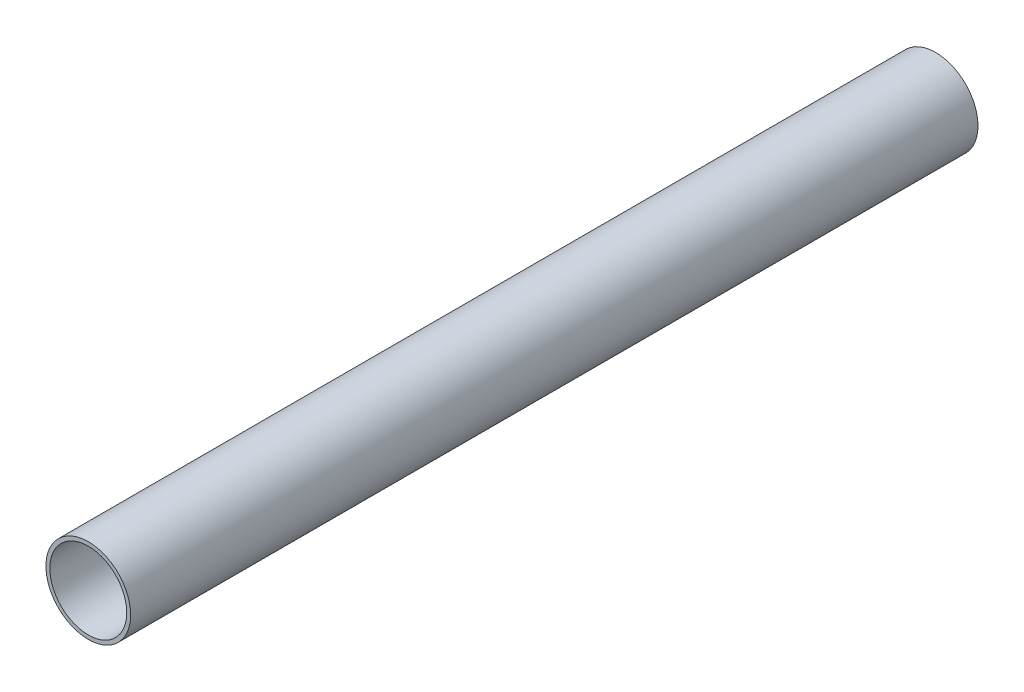
SolidWorks part; units mm, degrees
ref_plane "Ebene vorne" through (0, 0, 0) normal (0, 0, 1) x (1, 0, 0)
ref_plane "Ebene oben" through (0, 0, 0) normal (0, 1, 0) x (1, 0, 0)
ref_plane "Ebene rechts" through (0, 0, 0) normal (1, 0, 0) x (0, 0, -1)
sketch "Skizze1" plane through (0, 0, 0) normal (0, 0, 1) x (1, 0, 0)
  circle A0 centre (0, 0) radius 12.5
  circle A1 centre (0, 0) radius 11.35
  dimension "D1" = 25
  dimension "D2" = 1.15
extrude "Aufsatz-Linear austragen1" add sketch "Skizze1" along normal blind 250
